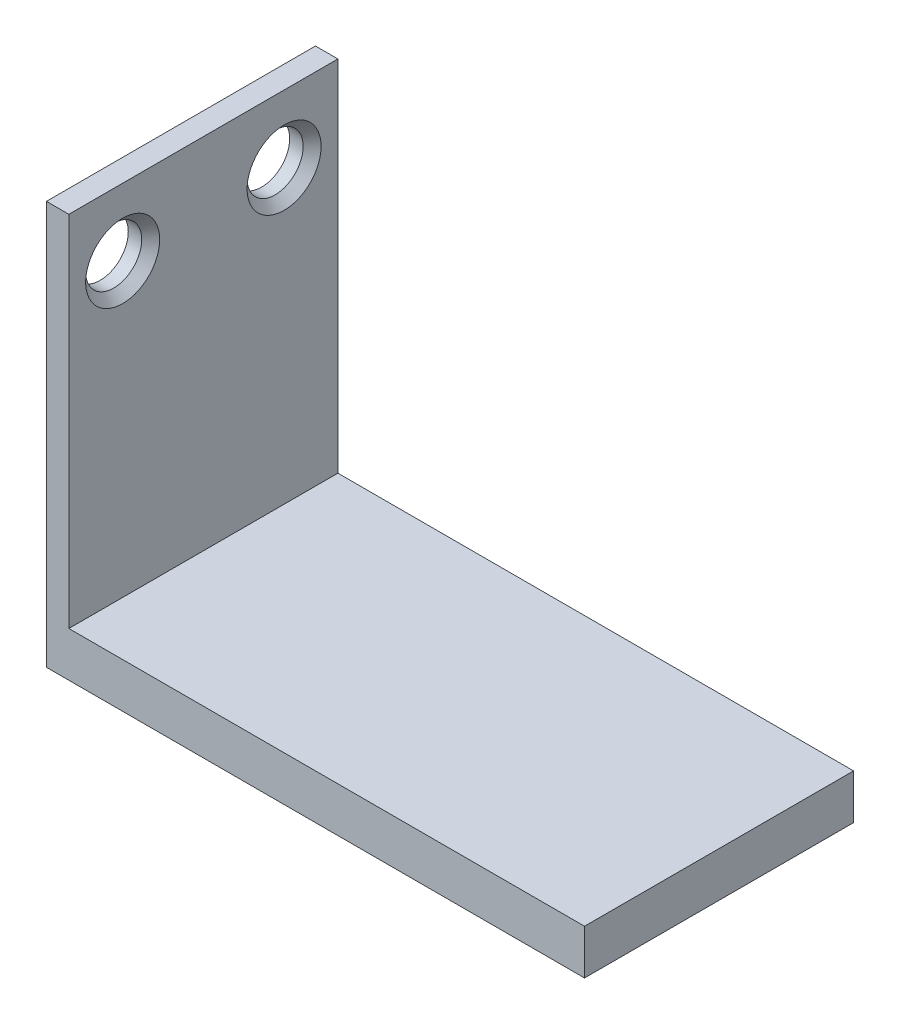
SolidWorks part; units mm, degrees
material "A-玻璃纤维"
ref_plane "前视基准面" through (0, 0, 0) normal (0, 0, 1) x (1, 0, 0)
ref_plane "上视基准面" through (0, 0, 0) normal (0, 1, 0) x (1, 0, 0)
ref_plane "右视基准面" through (0, 0, 0) normal (1, 0, 0) x (0, 0, -1)
sketch "草图1" plane through (0, 0, 0) normal (0, 1, 0) x (1, 0, 0)
  line L1 (-6, -3) -> (6, -3)
  line L2 (-6, -3) -> (-6, 3)
  line L3 (-6, 3) -> (6, 3)
  line L4 (6, -3) -> (6, 3)
  line L5 (-6, -3) -> (6, 3) construction
  line L6 (-6, 3) -> (6, -3) construction
  point P0 (0, 0)
  dimension "D1" = 12
  dimension "D2" = 6
extrude "凸台-拉伸1" add sketch "草图1" along normal blind 1 contours L2 L3 L4 L1
sketch "草图2" plane through (0, 1, 0) normal (0, 1, 0) x (1, 0, 0)
  line L0 (-6, -3) -> (6, -3) construction
  line L1 (-6, 3) -> (-5.5, 3)
  line L2 (-6, 3) -> (-6, -3)
  line L3 (-6, -3) -> (-5.5, -3)
  line L4 (-5.5, 3) -> (-5.5, -3)
  dimension "D1" = 0.5
extrude "凸台-拉伸2" add sketch "草图2" along normal blind 8
sketch "草图3" plane through (-5.5, 0, 0) normal (1, 0, 0) x (0, 0, -1)
  line L0 (-1.8, 7.5) -> (1.8, 7.5) construction
  line L1 (-3, 9) -> (-3, 1) construction
  line L2 (-3, 9) -> (3, 9) construction
  point P7 (-1.8, 7.5)
  point P8 (1.8, 7.5)
  dimension "D1" = 3.6
  dimension "D2" = 1.2
  dimension "D3" = 1.5
hole_wizard "M1.6 螺纹孔1" positions "草图4" profile "草图5" tap size "M1.6" standard "GB" end condition through all
sketch "草图4" plane through (-5.5, 0, 0) normal (1, 0, 0) x (0, 0, -1)
  line L0 (-1.8, 7.5) -> (1.8, 7.5) construction
  point P0 (1.8, 7.5)
  point P3 (-1.8, 7.5)
  dimension "D1" = 3.6
sketch "草图5" plane through (-5.5, 7.5, -1.8) normal (0, 1, 0) x (0, 0, -1)
  line L0 (0, 0) -> (0, 0.5)
  line L1 (0, 0.5) -> (0.625, 0.5)
  line L2 (0.625, 0.5) -> (0.625, 0.2)
  line L3 (0.625, 0.2) -> (0.825, 0)
  line L5 (0.825, 0) -> (0, 0)
  line L6 (-0.625, 0.2) -> (-0.825, 0) construction
  line L11 (0, -6.35) -> (0, 107.95) construction
  dimension "通孔螺纹孔钻头直径" = 1.25
  dimension "通孔螺纹孔钻头深度" = 0.5
  dimension "近端锥形沉头孔直径" = 1.65
  dimension "近端锥形沉头孔角度" = 90
